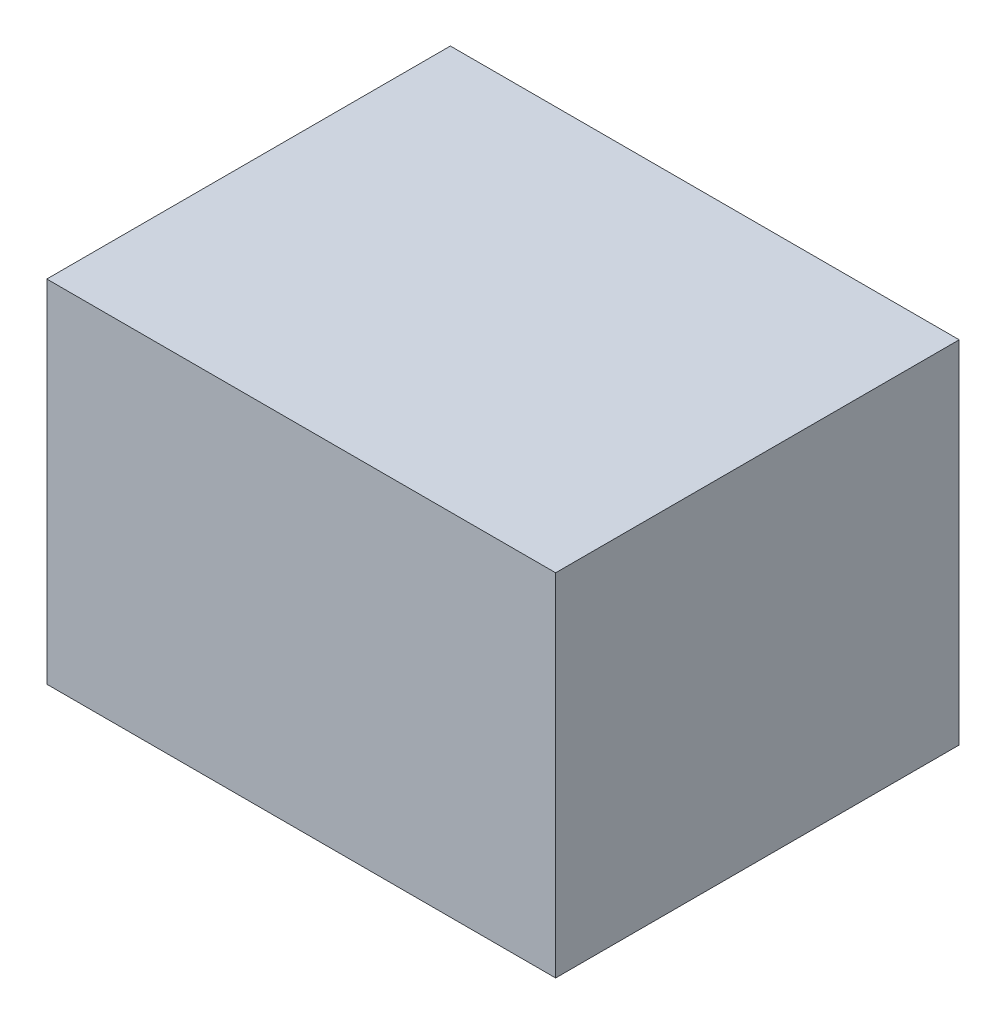
SolidWorks part; units mm, degrees
ref_plane "前视基准面" through (0, 0, 0) normal (0, 0, 1) x (1, 0, 0)
ref_plane "上视基准面" through (0, 0, 0) normal (0, 1, 0) x (1, 0, 0)
ref_plane "右视基准面" through (0, 0, 0) normal (1, 0, 0) x (0, 0, -1)
sketch "草图1" plane through (0, 0, 0) normal (0, 1, 0) x (1, 0, 0)
  line L1 (-145, 115) -> (145, 115)
  line L2 (-145, 115) -> (-145, -115)
  line L3 (-145, -115) -> (145, -115)
  line L4 (145, 115) -> (145, -115)
  line L5 (-145, 115) -> (145, -115) construction
  line L6 (-145, -115) -> (145, 115) construction
  point P0 (0, 0)
  dimension "D1" = 290
  dimension "D2" = 230
extrude "凸台-拉伸1" add sketch "草图1" along normal blind 200 contours L3 L4 L1 L2
